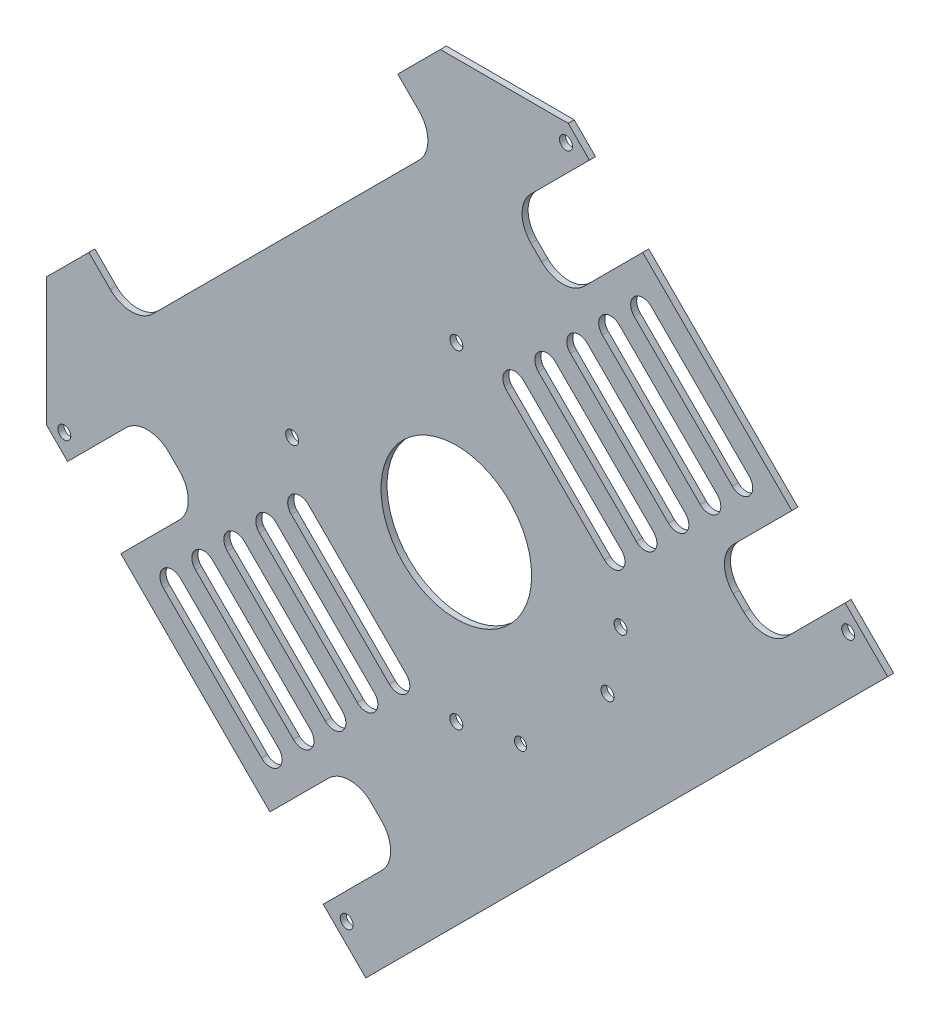
SolidWorks part; units mm, degrees
ref_plane "前视基准面" through (0, 0, 0) normal (0, 0, 1) x (1, 0, 0)
ref_plane "上视基准面" through (0, 0, 0) normal (0, 1, 0) x (1, 0, 0)
ref_plane "右视基准面" through (0, 0, 0) normal (1, 0, 0) x (0, 0, -1)
sketch "Sketch1" plane through (0, 0, 0) normal (0, 0, 1) x (1, 0, 0)
  line L16 (44.1941, 129.0469) -> (15.9098, 157.3312)
  line L17 (-110.8692, -62.3719) -> (-111.3693, -61.8718)
  line L18 (15.9098, 157.3312) -> (-19.4455, 121.9759)
  line L20 (61.1787, 112.0623) -> (111.3693, 61.8718)
  line L21 (-110.8692, -62.3719) -> (-61.8718, -111.3693)
  line L22 (143.1891, 30.052) -> (-30.052, -143.1891)
  line L23 (10.9602, -120.5617) -> (86.6206, -196.2221) construction
  line L24 (196.2221, -86.6206) -> (120.5617, -10.9602) construction
  line L25 (120.5617, -6.7176) -> (141.7749, 14.4956) construction
  line L26 (14.4956, 141.7749) -> (-6.7176, 120.5617) construction
  line L27 (61.1787, 112.0623) -> (61.8718, 111.3693)
  line L28 (44.1941, 129.0469) -> (17.6776, 102.5304)
  line L29 (61.8718, 111.3693) -> (35.3553, 84.8528)
  line L30 (17.6776, 102.5304) -> (35.3553, 84.8528)
  line L32 (111.3693, 61.8718) -> (84.8528, 35.3553)
  line L33 (129.0469, 44.1941) -> (102.5304, 17.6776)
  line L34 (84.8528, 35.3553) -> (102.5304, 17.6776)
  line L35 (56.5685, -56.5685) -> (-56.5685, 56.5685) construction
  line L36 (-35.3553, -84.8528) -> (-17.6776, -102.5304)
  line L37 (-44.1941, -129.0469) -> (-17.6776, -102.5304)
  line L38 (-61.8718, -111.3693) -> (-35.3553, -84.8528)
  line L40 (-102.5304, -17.6776) -> (-84.8528, -35.3553)
  line L41 (-111.3693, -61.8718) -> (-84.8528, -35.3553)
  line L42 (-129.0469, -44.1941) -> (-102.5304, -17.6776)
  line L44 (48.0832, 104.6517) -> (37.4766, 94.0451) construction
  line L45 (94.0451, 37.4766) -> (104.6517, 48.0832) construction
  line L46 (115.2584, 37.4766) -> (104.6517, 26.87) construction
  line L47 (102.5304, 24.7487) -> (98.9949, 28.2842) construction
  line L48 (28.2842, 98.9949) -> (24.7487, 102.5304) construction
  line L50 (-121.9759, 19.4455) -> (-107.8337, 5.3034)
  line L51 (-19.4455, 121.9759) -> (-5.3034, 107.8337)
  line L52 (-107.8337, 5.3034) -> (-5.3034, 107.8337)
  line L53 (-121.9759, 19.4455) -> (-157.3312, -15.9098)
  line L54 (129.0469, 44.1941) -> (143.1891, 30.052)
  line L55 (-129.0469, -44.1941) -> (-157.3312, -15.9098)
  line L56 (-44.1941, -129.0469) -> (-30.052, -143.1891)
  circle A4 centre (0, -54.5) radius 2.15
  circle A5 centre (54.5, 0) radius 2.15
  circle A6 centre (-54.5, 0) radius 2.15
  circle A7 centre (0, 54.5) radius 2.15
  circle A8 centre (0, 0) radius 25
  circle A9 centre (50.1675, -21.2948) radius 2.15 construction
  circle A10 centre (21.2948, -50.1675) radius 2 construction
  circle A11 centre (21.2948, -50.1675) radius 2
  circle A12 centre (50.1675, -21.2948) radius 2.15
  point P53 (99.3484, 42.7799)
  dimension "D1" = 45
  dimension "D2" = 45
  dimension "D3" = 10
  dimension "D4" = 10
  dimension "D5" = 5
  dimension "D6" = 5
  dimension "D7" = 5
  dimension "D8" = 5
  dimension "D9" = 5
  dimension "D10" = 5
  dimension "D11" = 20
  dimension "D12" = 50
  dimension "D13" = 50
extrude "Extrude1" add sketch "Sketch1" along normal blind 2 contours L22 L35 A8 L52 L50 L53 L55 L42 L40 L41 L17 L21 L38 L36 L37 L56 A4 A6 A11 | L35 L22 L54 L33 L34 L32 L20 L29 L30 L28 L16 L18 L51 L52 A8 A12 A7 A5
fillet "Fillet1" radius 10 2 edges at (-5.3034, 107.8337, 1) (-107.8337, 5.3034, 1)
fillet "Fillet2" radius 10 8 edges at (35.3553, 84.8528, 1) (17.6776, 102.5304, 1) (84.8528, 35.3553, 1) (102.5304, 17.6776, 1) (-17.6776, -102.5304, 1) (-35.3553, -84.8528, 1) (-84.8528, -35.3553, 1) (-102.5304, -17.6776, 1)
chamfer "Chamfer1" distance 30 angle 45 2 edges at (-157.3312, -15.9098, 1) (15.9098, 157.3312, 1)
sketch "Sketch3" plane through (0, 0, 2) normal (0, 0, 1) x (1, 0, 0)
  circle A0 centre (130.064, 36.3235) radius 2.15 construction
  circle A1 centre (36.3942, 130.1348) radius 2.15 construction
  circle A2 centre (-36.3942, -130.1348) radius 2.15 construction
  circle A3 centre (-130.1348, -36.3942) radius 2.15 construction
  circle A4 centre (130.064, 36.3235) radius 2.15
  circle A5 centre (36.3942, 130.1348) radius 2.15
  circle A6 centre (-36.3942, -130.1348) radius 2.15
  circle A7 centre (-130.1348, -36.3942) radius 2.15
extrude "Cut-Extrude1" cut sketch "Sketch3" against normal blind 3
sketch "Sketch4" plane through (0, 0, 2) normal (0, 0, 1) x (1, 0, 0)
  line L0 (61.8718, 94.3987) -> (94.3987, 61.8718) construction
  line L1 (64.7002, 97.2271) -> (97.2271, 64.7002)
  line L2 (59.0434, 91.5703) -> (91.5703, 59.0434)
  line L3 (111.3693, 61.8718) -> (91.9238, 42.4264) construction
  line L4 (61.8718, 111.3693) -> (42.4264, 91.9238) construction
  line L5 (61.8718, 111.3693) -> (111.3693, 61.8718) construction
  line L6 (-56.5685, 56.5685) -> (56.5685, -56.5685) construction
  line L7 (-100.7627, 12.3744) -> (-12.3744, 100.7627) construction
  line L8 (143.1891, 30.052) -> (-30.052, -143.1891) construction
  line L9 (51.2652, 83.7921) -> (83.7921, 51.2652) construction
  line L10 (54.0936, 86.6205) -> (86.6205, 54.0936)
  line L11 (48.4368, 80.9637) -> (80.9637, 48.4368)
  line L12 (40.6586, 73.1855) -> (73.1855, 40.6586) construction
  line L13 (43.487, 76.0139) -> (76.0139, 43.487)
  line L14 (37.8302, 70.3571) -> (70.3571, 37.8302)
  line L15 (30.052, 62.5789) -> (62.5789, 30.052) construction
  line L16 (32.8804, 65.4073) -> (65.4073, 32.8804)
  line L17 (27.2236, 59.7505) -> (59.7505, 27.2236)
  line L18 (19.4454, 51.9723) -> (51.9723, 19.4454) construction
  line L19 (22.2738, 54.8007) -> (54.8007, 22.2738)
  line L20 (16.617, 49.1439) -> (49.1439, 16.617)
  line L24 (-94.3987, -61.8718) -> (-61.8718, -94.3987) construction
  line L25 (-97.2271, -64.7002) -> (-64.7002, -97.2271)
  line L26 (-91.5703, -59.0434) -> (-59.0434, -91.5703)
  line L27 (-83.7921, -51.2652) -> (-51.2652, -83.7921) construction
  line L28 (-86.6205, -54.0936) -> (-54.0936, -86.6205)
  line L29 (-80.9637, -48.4368) -> (-48.4368, -80.9637)
  line L30 (-73.1855, -40.6586) -> (-40.6586, -73.1855) construction
  line L31 (-76.0139, -43.487) -> (-43.487, -76.0139)
  line L32 (-70.3571, -37.8302) -> (-37.8302, -70.3571)
  line L33 (-62.5789, -30.052) -> (-30.052, -62.5789) construction
  line L34 (-65.4073, -32.8804) -> (-32.8804, -65.4073)
  line L35 (-59.7505, -27.2236) -> (-27.2236, -59.7505)
  line L36 (-51.9723, -19.4454) -> (-19.4454, -51.9723) construction
  line L37 (-54.8007, -22.2738) -> (-22.2738, -54.8007)
  line L38 (-49.1439, -16.617) -> (-16.617, -49.1439)
  line L56 (8.8388, 41.3657) -> (41.3657, 8.8388) construction
  line L57 (11.6672, 44.1941) -> (44.1941, 11.6672)
  line L58 (6.0104, 38.5373) -> (38.5373, 6.0104)
  line L59 (8.8388, 41.3657) -> (41.3657, 8.8388) construction
  line L60 (11.6672, 44.1941) -> (44.1941, 11.6672)
  line L61 (6.0104, 38.5373) -> (38.5373, 6.0104)
  arc A0 (64.7002, 97.2271) -> (59.0434, 91.5703) centre (61.8718, 94.3987) ccw
  arc A1 (91.5703, 59.0434) -> (97.2271, 64.7002) centre (94.3987, 61.8718) ccw
  arc A2 (54.0936, 86.6205) -> (48.4368, 80.9637) centre (51.2652, 83.7921) ccw
  arc A3 (80.9637, 48.4368) -> (86.6205, 54.0936) centre (83.7921, 51.2652) ccw
  arc A4 (43.487, 76.0139) -> (37.8302, 70.3571) centre (40.6586, 73.1855) ccw
  arc A5 (70.3571, 37.8302) -> (76.0139, 43.487) centre (73.1855, 40.6586) ccw
  arc A6 (32.8804, 65.4073) -> (27.2236, 59.7505) centre (30.052, 62.5789) ccw
  arc A7 (59.7505, 27.2236) -> (65.4073, 32.8804) centre (62.5789, 30.052) ccw
  arc A8 (22.2738, 54.8007) -> (16.617, 49.1439) centre (19.4454, 51.9723) ccw
  arc A9 (49.1439, 16.617) -> (54.8007, 22.2738) centre (51.9723, 19.4454) ccw
  arc A12 (-97.2271, -64.7002) -> (-91.5703, -59.0434) centre (-94.3987, -61.8718) cw
  arc A13 (-59.0434, -91.5703) -> (-64.7002, -97.2271) centre (-61.8718, -94.3987) cw
  arc A14 (-86.6205, -54.0936) -> (-80.9637, -48.4368) centre (-83.7921, -51.2652) cw
  arc A15 (-48.4368, -80.9637) -> (-54.0936, -86.6205) centre (-51.2652, -83.7921) cw
  arc A16 (-76.0139, -43.487) -> (-70.3571, -37.8302) centre (-73.1855, -40.6586) cw
  arc A17 (-37.8302, -70.3571) -> (-43.487, -76.0139) centre (-40.6586, -73.1855) cw
  arc A18 (-65.4073, -32.8804) -> (-59.7505, -27.2236) centre (-62.5789, -30.052) cw
  arc A19 (-27.2236, -59.7505) -> (-32.8804, -65.4073) centre (-30.052, -62.5789) cw
  arc A20 (-54.8007, -22.2738) -> (-49.1439, -16.617) centre (-51.9723, -19.4454) cw
  arc A21 (-16.617, -49.1439) -> (-22.2738, -54.8007) centre (-19.4454, -51.9723) cw
  arc A36 (11.6672, 44.1941) -> (6.0104, 38.5373) centre (8.8388, 41.3657) ccw
  arc A37 (38.5373, 6.0104) -> (44.1941, 11.6672) centre (41.3657, 8.8388) ccw
  point P2 (78.1352, 78.1352)
  point P22 (67.5286, 67.5286)
  point P29 (56.922, 56.922)
  point P36 (46.3154, 46.3154)
  point P43 (35.7088, 35.7088)
  point P56 (-78.1352, -78.1352)
  point P63 (-67.5286, -67.5286)
  point P70 (-56.922, -56.922)
  point P77 (-46.3154, -46.3154)
  point P84 (-35.7088, -35.7088)
  point P91 (25.1022, 25.1022)
  point P98 (25.1022, 25.1022)
  point P105 (25.1022, 25.1022)
  point P112 (25.1022, 25.1022)
  point P119 (25.1022, 25.1022)
  point P126 (25.1022, 25.1022)
  point P133 (25.1022, 25.1022)
  dimension "D4" = 4
  dimension "D1" = 12
  dimension "D2" = 12
  dimension "D3" = 12
  dimension "D5" = 6
extrude "Cut-Extrude2" cut sketch "Sketch4" against normal blind 10
